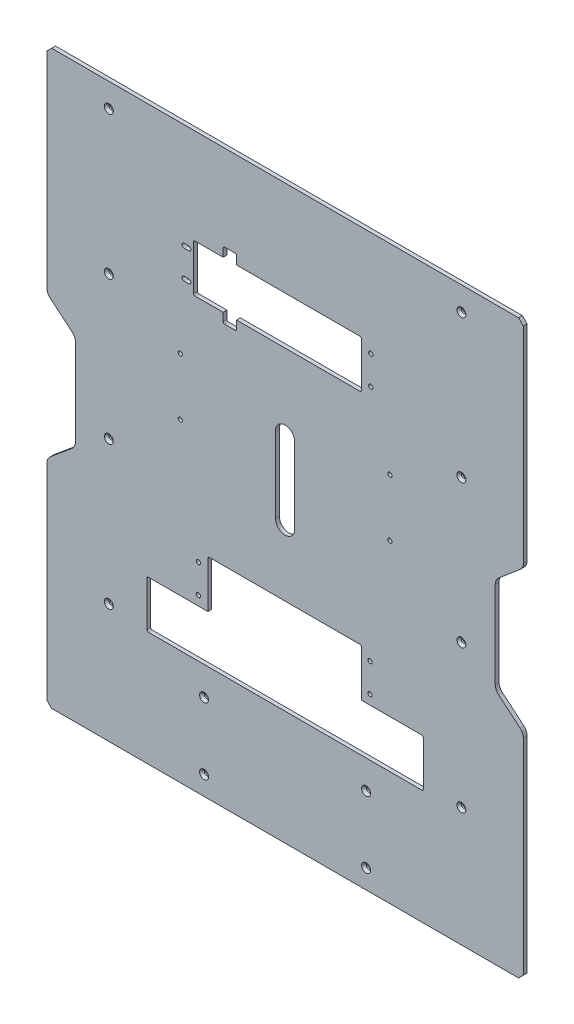
SolidWorks part; units mm, degrees
ref_plane "Piano frontale" through (0, 0, 0) normal (0, 0, 1) x (1, 0, 0)
ref_plane "Piano superiore" through (0, 0, 0) normal (0, 1, 0) x (1, 0, 0)
ref_plane "Piano destro" through (0, 0, 0) normal (1, 0, 0) x (0, 0, -1)
ref_plane "Piano1" through (0, 0, 4) normal (0, 0, 1) x (1, 0, 0)
sketch "Schizzo1" plane through (0, 0, 4) normal (0, 0, 1) x (1, 0, 0)
  line L0 (250, 300) -> (-250, 300)
  line L1 (-250, 300) -> (-250, -300)
  line L2 (-250, -300) -> (250, -300)
  line L3 (250, -300) -> (250, 300)
extrude "Estrusione-Estrusione1" add sketch "Schizzo1" against normal blind 4
sketch "Schizzo2" plane through (0, 0, 0) normal (0, 0, -1) x (-1, 0, 0)
  line L0 (250, -50) -> (250, 50)
  line L1 (250, 50) -> (220, 50)
  line L2 (220, 50) -> (220, -50)
  line L3 (220, -50) -> (250, -50)
extrude "Taglio-Estrusione1" cut sketch "Schizzo2" against normal through all
sketch "Schizzo3" plane through (0, 0, 0) normal (0, 0, -1) x (-1, 0, 0)
  line L0 (-250, 50) -> (-250, -50)
  line L1 (-250, -50) -> (-220.5131, -50)
  line L2 (-220.5131, -50) -> (-220.5131, 50)
  line L3 (-220.5131, 50) -> (-250, 50)
extrude "Taglio-Estrusione2" cut sketch "Schizzo3" against normal through all
sketch "Schizzo4" plane through (0, 0, 4) normal (0, 0, 1) x (1, 0, 0)
  line L0 (-145, -180) -> (145, -180)
  line L1 (145, -180) -> (145, -130)
  line L2 (145, -130) -> (80, -130)
  line L3 (80, -130) -> (80, -80)
  line L4 (80, -80) -> (-81, -80)
  line L5 (-81, -80) -> (-81, -130)
  line L6 (-81, -130) -> (-145, -130)
  line L7 (-145, -130) -> (-145, -180)
extrude "Taglio-Estrusione3" cut sketch "Schizzo4" against normal through all
sketch "Schizzo5" plane through (0, 0, 4) normal (0, 0, 1) x (1, 0, 0)
  line L0 (10, -10) -> (10, 70)
  line L1 (-10, 70) -> (-10, -10)
  arc A0 (-10, -10) -> (10, -10) centre (0, -10) ccw
  arc A1 (10, 70) -> (-10, 70) centre (0, 70) ccw
extrude "Taglio-Estrusione4" cut sketch "Schizzo5" against normal through all
sketch "Schizzo6" plane through (0, 0, 4) normal (0, 0, 1) x (1, 0, 0)
  line L0 (-101, 162.25) -> (-106, 162.25)
  line L1 (-106, 157.75) -> (-101, 157.75)
  arc A0 (-106, 162.25) -> (-106, 157.75) centre (-106, 160) ccw
  arc A1 (-101, 157.75) -> (-101, 162.25) centre (-101, 160) ccw
extrude "Taglio-Estrusione5" cut sketch "Schizzo6" against normal through all
sketch "Schizzo7" plane through (0, 0, 4) normal (0, 0, 1) x (1, 0, 0)
  line L0 (-101, 192.25) -> (-106, 192.25)
  line L1 (-106, 187.75) -> (-101, 187.75)
  arc A0 (-106, 192.25) -> (-106, 187.75) centre (-106, 190) ccw
  arc A1 (-101, 187.75) -> (-101, 192.25) centre (-101, 190) ccw
extrude "Taglio-Estrusione6" cut sketch "Schizzo7" against normal through all
sketch "Schizzo8" plane through (0, 0, 0) normal (0, 0, -1) x (-1, 0, 0)
  line L0 (65, 200) -> (65, 210)
  line L1 (65, 210) -> (51, 210)
  line L2 (51, 210) -> (51, 200)
  line L3 (51, 200) -> (-80, 200)
  line L4 (-80, 200) -> (-80, 150)
  line L5 (-80, 150) -> (51, 150)
  line L6 (51, 150) -> (51, 140)
  line L7 (51, 140) -> (65, 140)
  line L8 (65, 140) -> (65, 150)
  line L9 (65, 150) -> (96, 150)
  line L10 (96, 150) -> (96, 200)
  line L11 (96, 200) -> (65, 200)
extrude "Taglio-Estrusione7" cut sketch "Schizzo8" against normal through all
draft "Sformo1" type of draft neutral plane draft angle 40.292 faces to draft 2 face at (235.2566, 50, 2) face at (235.2566, -50, 2) neutral plane through (220.5131, -50, 4) neutral plane normal (1, 0, 0) parameters "D1"=40.292
draft "Sformo2" type of draft neutral plane draft angle 39.806 faces to draft 2 face at (-235, -50, 2) face at (-235, 50, 2) neutral plane through (-220, 50, 4) neutral plane normal (-1, 0, 0) parameters "D1"=39.806
hole_wizard "Foro Ø4.5 (4.5)-1" positions "Schizzo10" profile "Schizzo9" hole size "Ø4.5" standard "Ansi Metric"
sketch "Schizzo10" plane through (0, 0, 4) normal (0, 0, 1) x (1, 0, 0)
  point P0 (110, 90)
  point P1 (-110, 90)
  point P2 (110, 30)
  point P3 (-110, 30)
  point P4 (-91, -120)
  point P5 (-91, -90)
  point P6 (89, -120)
  point P7 (89, -90)
  point P8 (90, 190)
  point P9 (90, 160)
sketch "Schizzo9" plane through (110, 90, 4) normal (1, 0, 0) x (0, -1, 0)
  line L0 (0, 0) -> (0, 4)
  line L1 (0, 4) -> (2.25, 4)
  line L2 (2.25, 4) -> (2.25, 0)
  line L5 (2.25, 0) -> (0, 0)
  line L11 (0, -6.35) -> (0, 107.95) construction
  dimension "Thru Hole Dia." = 4.5
  dimension "Thru Hole Depth" = 4
hole_wizard "Foro svasato per Vite M4-1" positions "Schizzo12" profile "Schizzo11" countersink size "M4" standard "Ansi Metric"
sketch "Schizzo12" plane through (0, 0, 4) normal (0, 0, 1) x (1, 0, 0)
  point P0 (-185, -175)
  point P1 (-185, -25)
  point P2 (-185, 125)
  point P3 (-185, 275)
  point P4 (185, -175)
  point P5 (185, -25)
  point P6 (185, 125)
  point P7 (185, 275)
  point P8 (-85, -210)
  point P9 (85, -210)
  point P10 (85, -280)
  point P11 (-85, -280)
sketch "Schizzo11" plane through (-185, -175, 4) normal (1, 0, 0) x (0, -1, 0)
  line L0 (0, 0) -> (0, 4)
  line L1 (0, 4) -> (2.25, 4)
  line L2 (2.25, 4) -> (2.25, 2.45)
  line L3 (2.25, 2.45) -> (4.7, 0)
  line L5 (4.7, 0) -> (0, 0)
  line L6 (-2.25, 2.45) -> (-4.7, 0) construction
  line L11 (0, -6.35) -> (0, 107.95) construction
  dimension "Thru Hole Dia." = 4.5
  dimension "Thru Hole Depth" = 4
  dimension "Near C'Sink Dia." = 9.4
  dimension "Near C'Sink Angle" = 90
chamfer "Smusso1" distance 5 angle 45 4 edges at (-250, 300, 2) (250, 300, 2) (-250, -300, 2) (250, -300, 2)
fillet "Raccordo1" radius 1.5 14 edges at (80, 150, 2) (-145, -130, 2) (145, -180, 2) (-65, 140, 2) (80, -80, 2) (-96, 150, 2) (145, -130, 2) (-96, 200, 2) (-145, -180, 2) (-51, 140, 2) (-81, -80, 2) (-51, 210, 2) (80, 200, 2) (-65, 210, 2)
fillet "Raccordo2" radius 10 8 edges at (250, 75, 2) (220.5131, -50, 2) (250, -75, 2) (-220, 50, 2) (220.5131, 50, 2) (-220, -50, 2) (-250, -75, 2) (-250, 75, 2)
